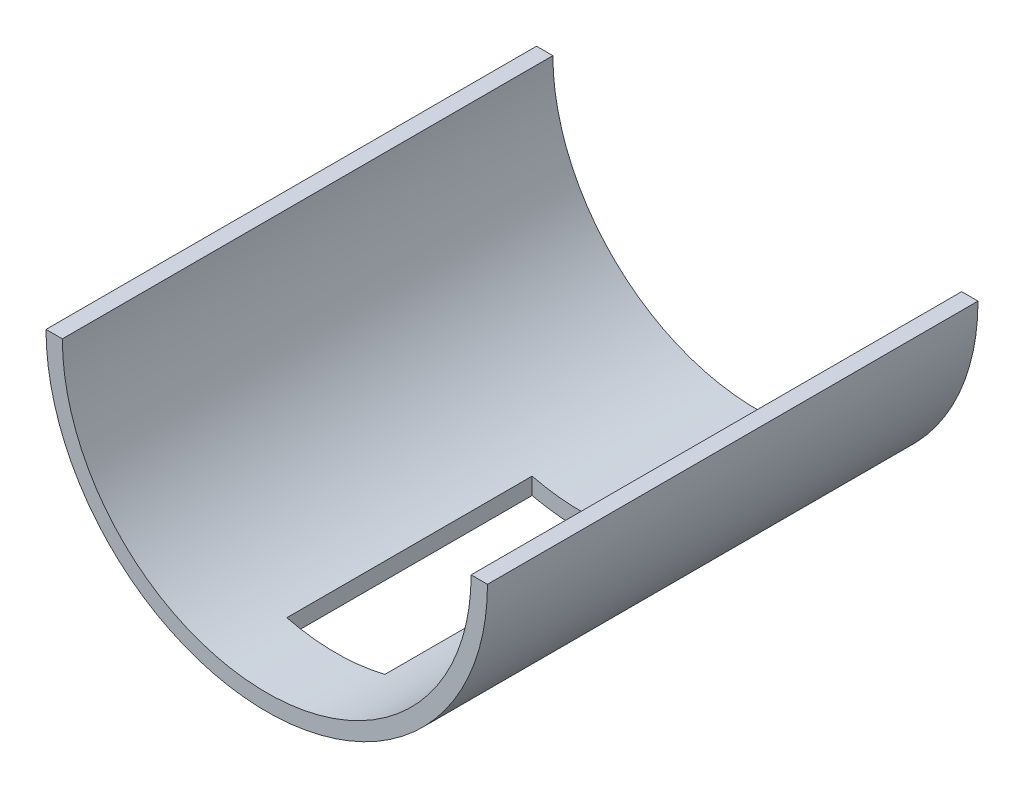
SolidWorks part; units mm, degrees
ref_plane "Plan de face" through (0, 0, 0) normal (0, 0, 1) x (1, 0, 0)
ref_plane "Plan de dessus" through (0, 0, 0) normal (0, 1, 0) x (1, 0, 0)
ref_plane "Plan de droite" through (0, 0, 0) normal (1, 0, 0) x (0, 0, -1)
sketch "Esquisse1" plane through (0, 0, 0) normal (0, 0, 1) x (1, 0, 0)
  line L0 (-27, 0) -> (-25, 0)
  line L1 (25, 0) -> (27, 0)
  arc A0 (27, 0) -> (-27, 0) centre (0, 0) cw
  arc A1 (25, 0) -> (-25, 0) centre (0, 0) cw
  dimension "D1" = 25
  dimension "D2" = 27
extrude "Boss.-Extru.1" add sketch "Esquisse1" along normal blind 60
sketch "Esquisse2" plane through (0, 0, 0) normal (0, 1, 0) x (1, 0, 0)
  line L1 (-6, -21.545) -> (6, -21.545)
  line L2 (-6, -21.545) -> (-6, -51.545)
  line L3 (-6, -51.545) -> (6, -51.545)
  line L4 (6, -21.545) -> (6, -51.545)
  line L5 (-6, -21.545) -> (6, -51.545) construction
  line L6 (-6, -51.545) -> (6, -21.545) construction
  point P0 (0, -36.545)
  dimension "D1" = 12
  dimension "D2" = 30
extrude "Enlèv. mat.-Extru.1" cut sketch "Esquisse2" against normal through all
